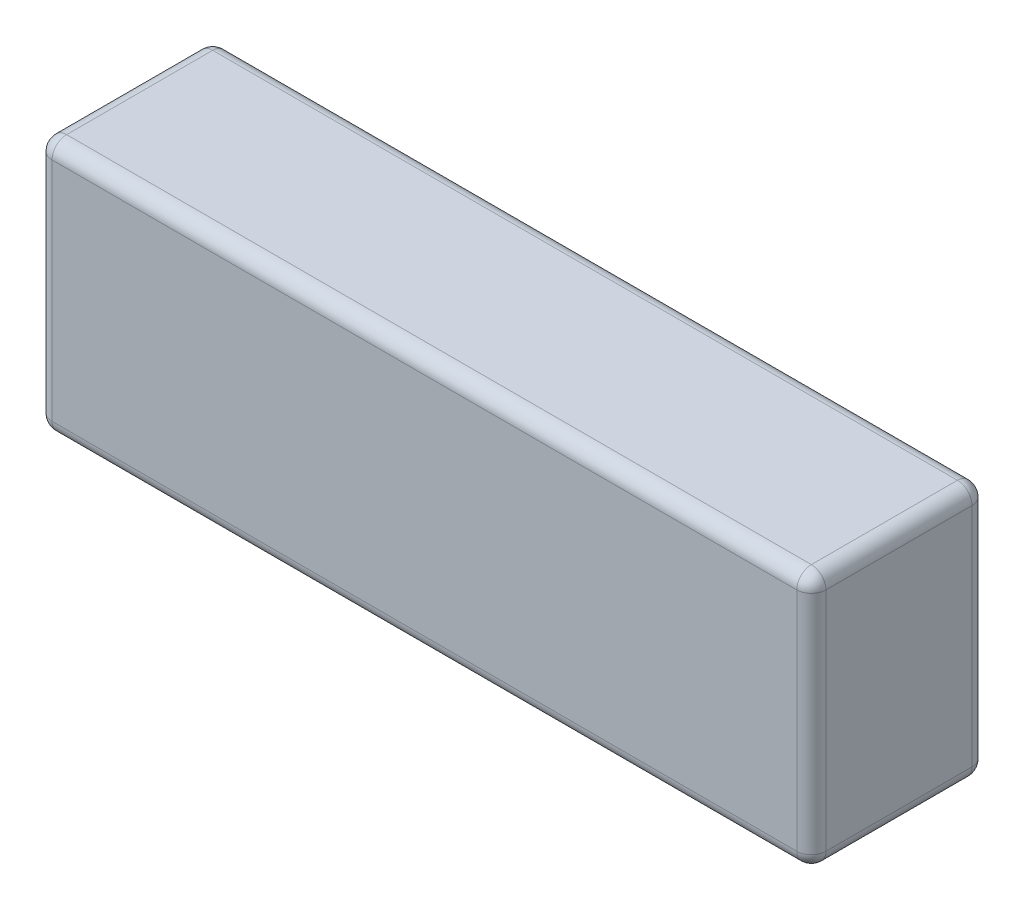
SolidWorks part; units mm, degrees
ref_plane "Front Plane" through (0, 0, 0) normal (0, 0, 1) x (1, 0, 0)
ref_plane "Top Plane" through (0, 0, 0) normal (0, 1, 0) x (1, 0, 0)
ref_plane "Right Plane" through (0, 0, 0) normal (1, 0, 0) x (0, 0, -1)
sketch "Sketch1" plane through (0, 0, 0) normal (0, 1, 0) x (1, 0, 0)
  line L0 (-62.565, 22.808) -> (43.435, 22.808)
  line L5 (43.435, 22.808) -> (43.435, -1.192)
  line L6 (-62.565, 22.808) -> (-62.565, -1.192)
  line L7 (43.435, -1.192) -> (-62.565, -1.192)
extrude "Boss-Extrude1" add sketch "Sketch1" along normal blind 35
fillet "Fillet1" radius 2 12 edges at (-62.565, 17.5, 1.192) (-62.565, 0, -10.808) (-62.565, 35, -10.808) (-62.565, 17.5, -22.808) (-9.565, 35, -22.808) (-9.565, 0, -22.808) (-9.565, 0, 1.192) (43.435, 0, -10.808) (43.435, 17.5, -22.808) (43.435, 35, -10.808) (43.435, 17.5, 1.192) (-9.565, 35, 1.192)
sketch "Sketch2" plane through (-62.565, 0, 0) normal (-1, 0, 0) x (0, 0, 1)
  circle A0 centre (-11.4465, 18.7208) radius 7.9888
extrude "Boss-Extrude2" add sketch "Sketch2" along normal blind 1
